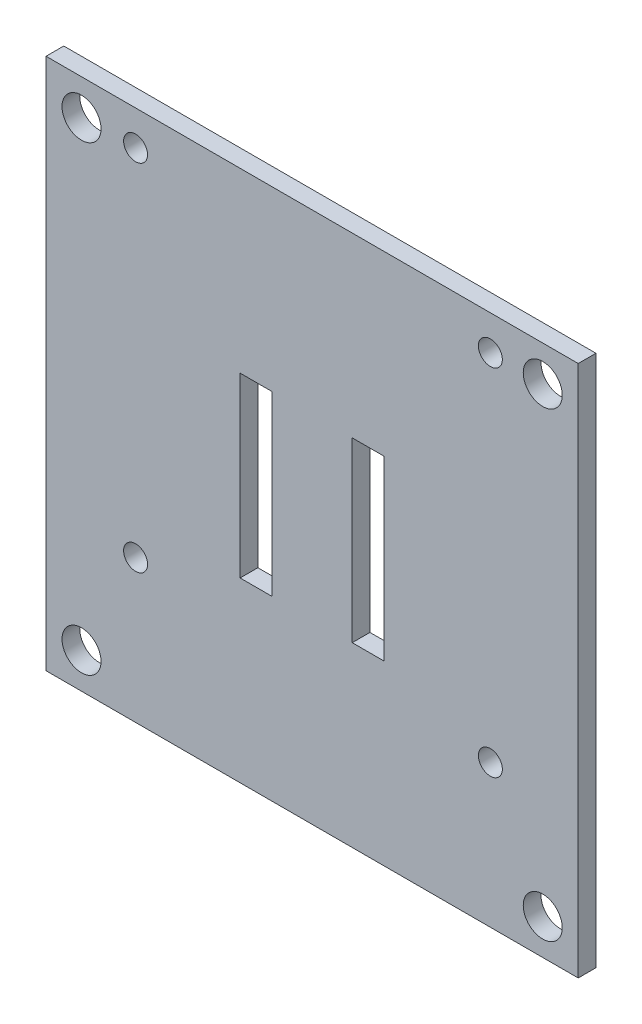
SolidWorks part; units mm, degrees
ref_plane "Front Plane" through (0, 0, 0) normal (0, 0, 1) x (1, 0, 0)
ref_plane "Top Plane" through (0, 0, 0) normal (0, 1, 0) x (1, 0, 0)
ref_plane "Right Plane" through (0, 0, 0) normal (1, 0, 0) x (0, 0, -1)
sketch "Sketch2" plane through (0, 0, 0) normal (0, 0, 1) x (1, 0, 0)
  line L1 (-38.1, -38.1) -> (38.1, -38.1)
  line L2 (-38.1, -38.1) -> (-38.1, 38.1)
  line L3 (-38.1, 38.1) -> (38.1, 38.1)
  line L4 (38.1, -38.1) -> (38.1, 38.1)
  line L5 (-38.1, -38.1) -> (38.1, 38.1) construction
  line L6 (-38.1, 38.1) -> (38.1, -38.1) construction
  point P0 (0, 0)
  dimension "D1" = 76.2
  dimension "D2" = 76.2
extrude "Boss-Extrude1" add sketch "Sketch2" along normal blind 2.54
sketch "Sketch6" plane through (0, 0, 0) normal (0, 0, -1) x (-1, 0, 0)
  line L1 (-25.5217, 33.1487) -> (25.2783, 33.1487)
  line L2 (-25.5217, 33.1487) -> (-25.5217, -17.6513)
  line L3 (-25.5217, -17.6513) -> (25.2783, -17.6513)
  line L4 (25.2783, 33.1487) -> (25.2783, -17.6513)
  line L5 (-25.5217, 33.1487) -> (25.2783, -17.6513) construction
  line L6 (-25.5217, -17.6513) -> (25.2783, 33.1487) construction
  line L7 (33.02, 33.02) -> (-33.02, 33.02)
  line L8 (33.02, 33.02) -> (33.02, -33.02)
  line L9 (33.02, -33.02) -> (-33.02, -33.02)
  line L10 (-33.02, 33.02) -> (-33.02, -33.02)
  line L11 (33.02, 33.02) -> (-33.02, -33.02) construction
  line L12 (33.02, -33.02) -> (-33.02, 33.02) construction
  circle A0 centre (33.02, 33.02) radius 2.794
  circle A1 centre (-33.02, 33.02) radius 2.794
  circle A2 centre (-33.02, -33.02) radius 2.794
  circle A3 centre (33.02, -33.02) radius 2.794
  point P0 (-0.1217, 7.7487)
  point P7 (0, 0)
  dimension "D5" = 5.588
  dimension "D6" = 5.588
  dimension "D7" = 5.588
  dimension "D8" = 5.588
  dimension "D1" = 50.8
  dimension "D2" = 50.8
  dimension "D3" = 66.04
  dimension "D4" = 66.04
sketch "Sketch7" plane through (0, 0, 0) normal (0, 0, -1) x (-1, 0, 0)
  circle A0 centre (25.2783, -17.6513) radius 1.7145
  circle A1 centre (25.2783, 33.1487) radius 1.7145
  circle A2 centre (-25.5217, 33.1487) radius 1.7145
  circle A3 centre (-25.5217, -17.6513) radius 1.7145
  dimension "D1" = 3.429
  dimension "D2" = 3.429
  dimension "D3" = 3.429
  dimension "D4" = 3.429
extrude "Cut-Extrude1" cut sketch "Sketch7" against normal blind 5.08
sketch "Sketch9" plane through (0, 0, 2.54) normal (0, 0, 1) x (1, 0, 0)
  line L0 (0, -38.1) -> (0, 38.1) construction
  line L1 (-38.1, -38.1) -> (38.1, -38.1) construction
  line L2 (38.1, 38.1) -> (-38.1, 38.1) construction
  line L3 (38.1, 0) -> (-38.1, 0) construction
  line L4 (38.1, -38.1) -> (38.1, 38.1) construction
  line L5 (-38.1, 38.1) -> (-38.1, -38.1) construction
  line L6 (-10.3097, -12.7) -> (-5.7377, 12.7) construction
  line L7 (10.3097, 12.7) -> (5.7377, 12.7)
  line L8 (10.3097, 12.7) -> (10.3097, -12.7)
  line L9 (10.3097, -12.7) -> (5.7377, -12.7)
  line L10 (5.7377, 12.7) -> (5.7377, -12.7)
  line L11 (10.3097, 12.7) -> (5.7377, -12.7) construction
  line L12 (10.3097, -12.7) -> (5.7377, 12.7) construction
  line L13 (-10.3097, 12.7) -> (-5.7377, -12.7) construction
  line L14 (-5.7377, 12.7) -> (-5.7377, -12.7)
  line L15 (-10.3097, -12.7) -> (-5.7377, -12.7)
  line L16 (-10.3097, 12.7) -> (-10.3097, -12.7)
  line L17 (-10.3097, 12.7) -> (-5.7377, 12.7)
  point P12 (8.0237, 0)
  point P21 (-8.0237, 0)
  dimension "D1" = 25.4
  dimension "D2" = 4.572
extrude "Cut-Extrude2" cut sketch "Sketch9" against normal blind 5.08
extrude "Cut-Extrude3" cut sketch "Sketch6" against normal blind 5.08 contours A0 | A3 | A2 | A1
